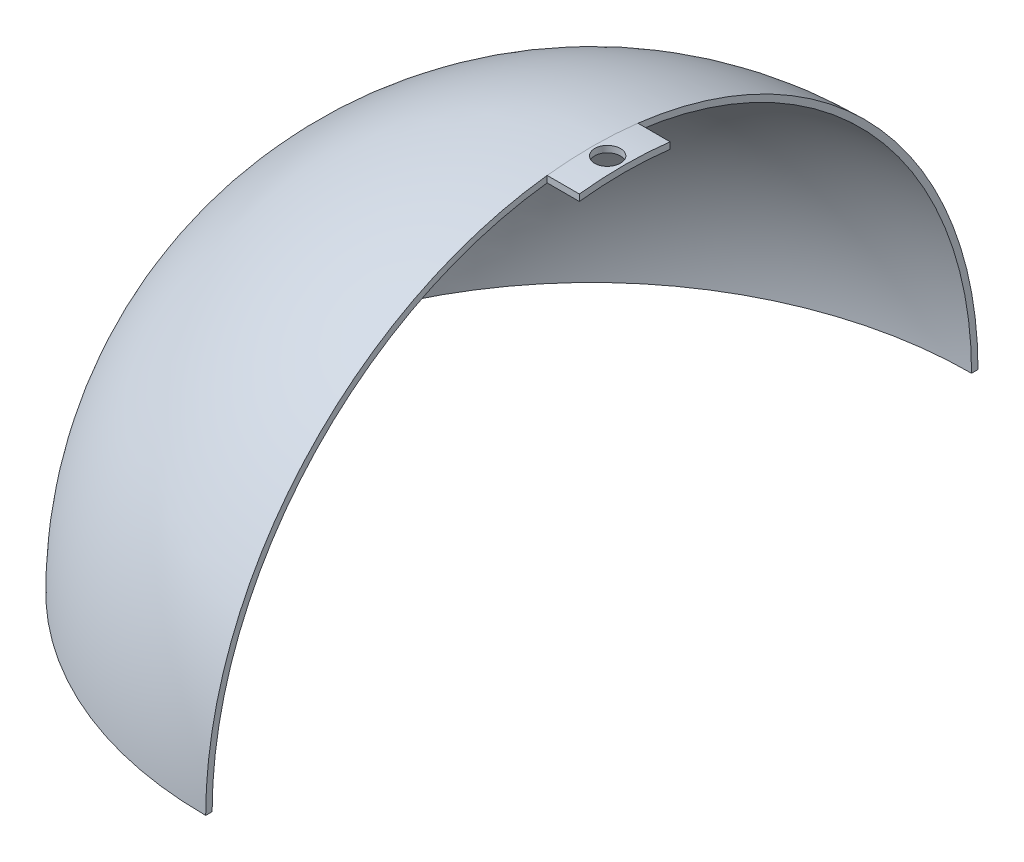
SolidWorks part; units mm, degrees
ref_plane "Front" through (0, 0, 0) normal (0, 0, 1) x (1, 0, 0)
ref_plane "Top" through (0, 0, 0) normal (0, 1, 0) x (1, 0, 0)
ref_plane "Right" through (0, 0, 0) normal (1, 0, 0) x (0, 0, -1)
sketch "Sketch2" plane through (0, 0, 0) normal (0, 1, 0) x (1, 0, 0)
  line L0 (0, -12000) -> (0, -11800)
  line L1 (0, 11800) -> (0, 12000)
  line L2 (0, -3077.1526) -> (0, 2858.4717) construction
  line L3 (0, -13200) -> (0, 13200) construction
  arc A0 (0, 11800) -> (0, -11800) centre (0, 0) ccw
  arc A1 (0, 12000) -> (0, -12000) centre (0, 0) ccw
  dimension "D1" = 12000
  dimension "D2" = 11800
revolve "Revolve1" add sketch "Sketch2" angle 90 about L2
sketch "Sketch4" plane through (0, 0, 0) normal (1, 0, 0) x (0, 0, -1)
  line L0 (-1388.2786, 11718.0494) -> (-1388.2786, 11919.4246)
  line L1 (1431.7214, 11914.2844) -> (1431.7214, 11712.8209)
  arc A0 (-1388.2786, 11718.0494) -> (1431.7214, 11712.8209) centre (0, 0) cw
  arc A1 (11800, 0) -> (-11800, 0) centre (0, 0) ccw construction
  arc A2 (-1388.2786, 11919.4246) -> (1431.7214, 11914.2844) centre (0, 0) cw
  arc A3 (12000, 0) -> (-12000, 0) centre (0, 0) ccw construction
  dimension "D1" = 2820
extrude "Boss-Extrude1" add sketch "Sketch4" along normal blind 1000
ref_plane "Plane1" through (0, 12000, 0) normal (0, 1, 0) x (1, 0, 0)
sketch "Sketch5" plane through (0, 12000, 0) normal (0, 1, 0) x (1, 0, 0)
  line L0 (-6600, 0) -> (6600, 0) construction
  circle A0 centre (491.6743, 0) radius 400
extrude "Cut-Extrude1" cut sketch "Sketch5" against normal blind 1000
